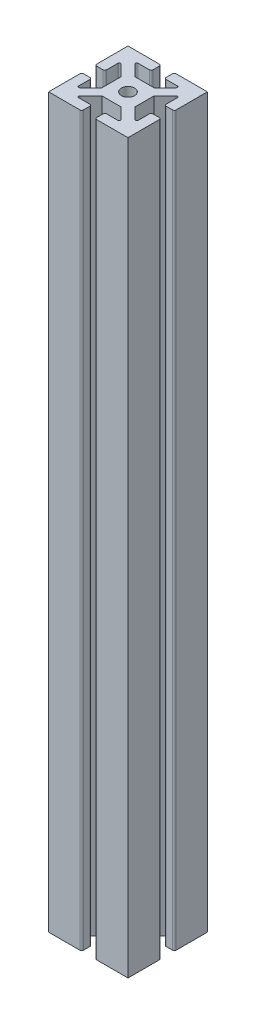
SolidWorks part; units mm, degrees
ref_plane "Front Plane" through (0, 0, 0) normal (0, 0, 1) x (1, 0, 0)
ref_plane "Top Plane" through (0, 0, 0) normal (0, 1, 0) x (1, 0, 0)
ref_plane "Right Plane" through (0, 0, 0) normal (1, 0, 0) x (0, 0, -1)
sketch "Sketch1" plane through (0, 0, 0) normal (0, 1, 0) x (1, 0, 0)
  line L0 (1.25, 6) -> (6, 6)
  line L1 (-6, -6) -> (-1.25, -6)
  line L2 (-6, -6) -> (-6, -1.25)
  line L3 (-6, 6) -> (-1.25, 6)
  line L4 (6, -6) -> (6, -1.25)
  line L5 (-1, 5.75) -> (-1, 4.75)
  line L6 (1, 5.75) -> (1, 4.75)
  line L8 (-4.5, -2.9735) -> (-4.5, -1.25)
  line L9 (-2.9735, 4.5) -> (-1.25, 4.5)
  line L10 (4.5, -2.9735) -> (4.5, -1.25)
  line L11 (1.25, 4.5) -> (2.9735, 4.5)
  line L12 (-3.1099, 4.1706) -> (-1.4393, 2.5)
  line L13 (-1.4393, -2.5) -> (1.4393, -2.5)
  line L14 (-2.5, -1.4393) -> (-2.5, 1.4393)
  line L15 (-1.4393, 2.5) -> (1.4393, 2.5)
  line L16 (2.5, -1.4393) -> (2.5, 1.4393)
  line L18 (-4.1706, 3.1099) -> (-2.5, 1.4393)
  line L20 (0, -55) -> (0, 55) construction
  line L21 (4.1706, 3.1099) -> (2.5, 1.4393)
  line L22 (3.1099, 4.1706) -> (1.4393, 2.5)
  line L23 (-55, 0) -> (55, 0) construction
  line L24 (4.1706, -3.1099) -> (2.5, -1.4393)
  line L25 (3.1099, -4.1706) -> (1.4393, -2.5)
  line L26 (-4.1706, -3.1099) -> (-2.5, -1.4393)
  line L27 (-3.1099, -4.1706) -> (-1.4393, -2.5)
  line L28 (-2.9735, -4.5) -> (-1.25, -4.5)
  line L29 (1, -5.75) -> (1, -4.75)
  line L30 (-1, -5.75) -> (-1, -4.75)
  line L31 (1.25, -6) -> (6, -6)
  line L32 (1.25, -4.5) -> (2.9735, -4.5)
  line L33 (-6, 1.25) -> (-6, 6)
  line L34 (-5.75, 1) -> (-4.75, 1)
  line L35 (-5.75, -1) -> (-4.75, -1)
  line L36 (-4.5, 1.25) -> (-4.5, 2.9735)
  line L37 (5.75, -1) -> (4.75, -1)
  line L38 (5.75, 1) -> (4.75, 1)
  line L39 (6, 1.25) -> (6, 6)
  line L40 (4.5, 1.25) -> (4.5, 2.9735)
  circle A0 centre (0, 0) radius 1
  arc A1 (1, 4.75) -> (1.25, 4.5) centre (1.25, 4.75) ccw
  arc A2 (1, 5.75) -> (1.25, 6) centre (1.25, 5.75) cw
  arc A3 (-1, 5.75) -> (-1.25, 6) centre (-1.25, 5.75) ccw
  arc A4 (-1.25, 4.5) -> (-1, 4.75) centre (-1.25, 4.75) ccw
  arc A5 (-4.1706, 3.1099) -> (-4.5, 2.9735) centre (-4.307, 2.9735) ccw
  arc A6 (-3.1099, 4.1706) -> (-2.9735, 4.5) centre (-2.9735, 4.307) cw
  arc A7 (4.1706, 3.1099) -> (4.5, 2.9735) centre (4.307, 2.9735) cw
  arc A8 (3.1099, 4.1706) -> (2.9735, 4.5) centre (2.9735, 4.307) ccw
  arc A9 (4.1706, -3.1099) -> (4.5, -2.9735) centre (4.307, -2.9735) ccw
  arc A10 (3.1099, -4.1706) -> (2.9735, -4.5) centre (2.9735, -4.307) cw
  arc A11 (-3.1099, -4.1706) -> (-2.9735, -4.5) centre (-2.9735, -4.307) ccw
  arc A12 (-4.1706, -3.1099) -> (-4.5, -2.9735) centre (-4.307, -2.9735) cw
  arc A13 (1, -4.75) -> (1.25, -4.5) centre (1.25, -4.75) cw
  arc A14 (-1.25, -4.5) -> (-1, -4.75) centre (-1.25, -4.75) cw
  arc A15 (1, -5.75) -> (1.25, -6) centre (1.25, -5.75) ccw
  arc A16 (-1, -5.75) -> (-1.25, -6) centre (-1.25, -5.75) cw
  arc A17 (-4.5, 1.25) -> (-4.75, 1) centre (-4.75, 1.25) cw
  arc A18 (-4.5, -1.25) -> (-4.75, -1) centre (-4.75, -1.25) ccw
  arc A19 (-6, -1.25) -> (-5.75, -1) centre (-5.75, -1.25) cw
  arc A20 (-6, 1.25) -> (-5.75, 1) centre (-5.75, 1.25) ccw
  arc A21 (4.5, -1.25) -> (4.75, -1) centre (4.75, -1.25) cw
  arc A22 (6, -1.25) -> (5.75, -1) centre (5.75, -1.25) ccw
  arc A23 (4.5, 1.25) -> (4.75, 1) centre (4.75, 1.25) ccw
  arc A24 (6, 1.25) -> (5.75, 1) centre (5.75, 1.25) cw
  point P0 (0, 0)
  point P6 (0, 0)
  point P11 (0, 0)
  point P23 (-4.5, 1)
  point P31 (1, 4.5)
  point P34 (1, 6)
  point P37 (-1, 6)
  point P85 (-6, -1)
  point P88 (-6, 1)
  dimension "D2" = 2
  dimension "D8" = 2
  dimension "D9" = 0.25
  dimension "D4" = 0.25
  dimension "D1" = 2
  dimension "D3" = 12
  dimension "D5" = 12
extrude "Boss-Extrude1" add sketch "Sketch1" along normal blind 110
